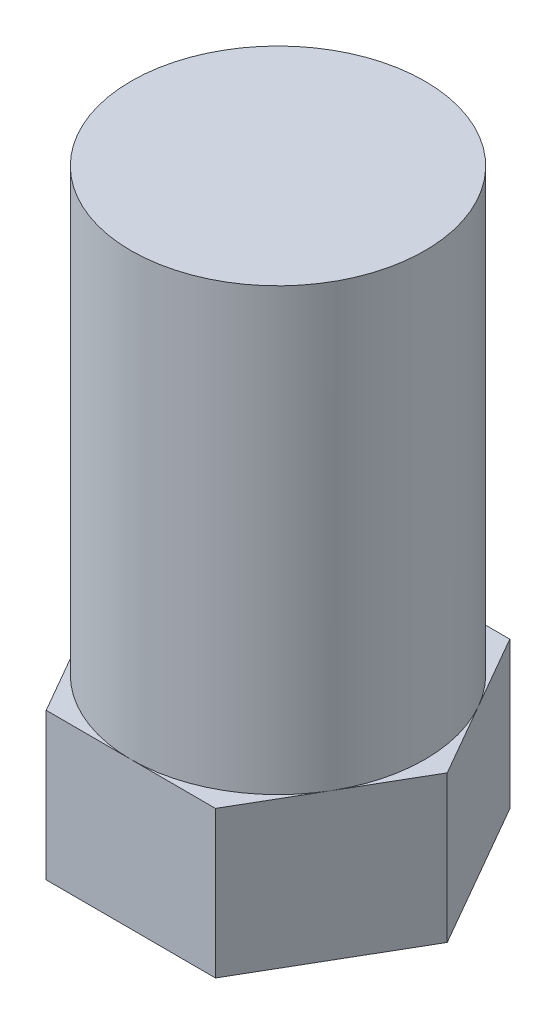
SolidWorks part; units mm, degrees
ref_plane "Alzado" through (0, 0, 0) normal (0, 0, 1) x (1, 0, 0)
ref_plane "Planta" through (0, 0, 0) normal (0, 1, 0) x (1, 0, 0)
ref_plane "Vista lateral" through (0, 0, 0) normal (1, 0, 0) x (0, 0, -1)
sketch "Croquis1" plane through (0, 0, 0) normal (0, 1, 0) x (1, 0, 0)
  line L1 (2.8971, 4.994) -> (-2.8764, 5.006)
  line L2 (-2.8764, 5.006) -> (-5.7735, 0.0119)
  line L3 (-5.7735, 0.0119) -> (-2.8971, -4.994)
  line L4 (-2.8971, -4.994) -> (2.8764, -5.006)
  line L5 (2.8764, -5.006) -> (5.7735, -0.0119)
  line L6 (5.7735, -0.0119) -> (2.8971, 4.994)
  circle A0 centre (0, 0) radius 5 construction
extrude "Saliente-Extruir1" add sketch "Croquis1" along normal blind 5
sketch "Croquis2" plane through (0, 5, 0) normal (0, 1, 0) x (1, 0, 0)
  circle A0 centre (0, 0) radius 5
extrude "Saliente-Extruir2" add sketch "Croquis2" along normal blind 15
